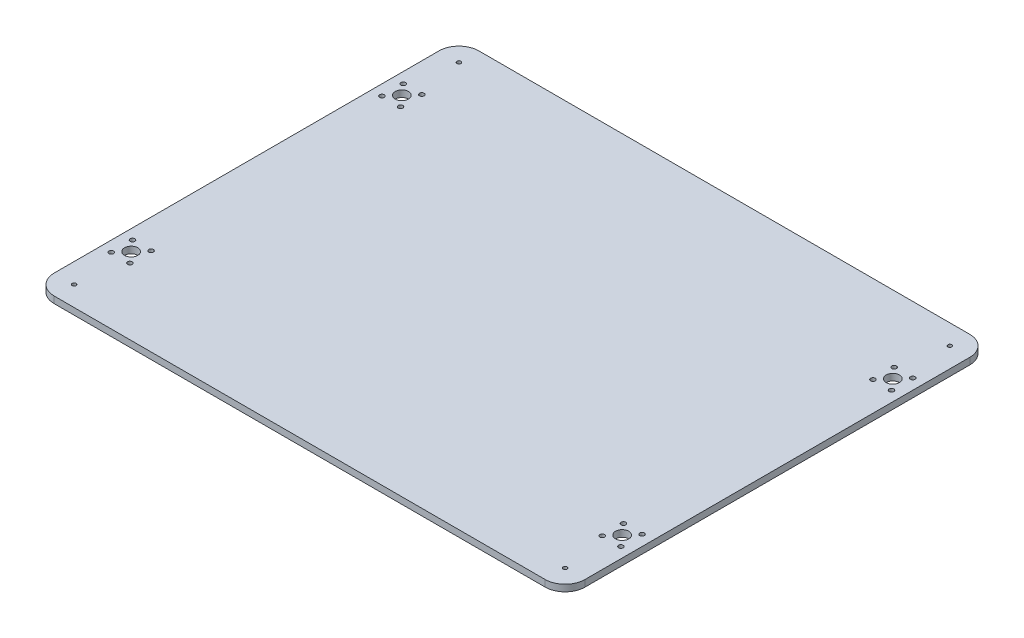
SolidWorks part; units mm, degrees
ref_plane "前视基准面" through (0, 0, 0) normal (0, 0, 1) x (1, 0, 0)
ref_plane "上视基准面" through (0, 0, 0) normal (0, 1, 0) x (1, 0, 0)
ref_plane "右视基准面" through (0, 0, 0) normal (1, 0, 0) x (0, 0, -1)
other "Configuration Table"
sketch "草图1" plane through (0, 0, 0) normal (0, 1, 0) x (1, 0, 0)
  line L0 (0, 160) -> (0, -160) construction
  line L1 (200, 0) -> (200, -160)
  line L2 (-200, 0) -> (-200, 160)
  line L3 (-200, 160) -> (200, 160)
  line L4 (-200, 0) -> (-200, -160)
  line L5 (-200, -160) -> (200, -160)
  line L6 (200, 0) -> (200, 160)
  point P0 (0, 0)
  dimension "D1" = 160
  dimension "D2" = 160
  dimension "D3" = 200
extrude "凸台-拉伸1" add sketch "草图1" along normal blind 5
fillet "圆角1" radius 15 4 edges at (-200, 2.5, -160) (-200, 2.5, 160) (200, 2.5, 160) (200, 2.5, -160)
sketch "草图2" plane through (0, 5, 0) normal (0, 1, 0) x (1, 0, 0)
  line L0 (0, -249.0197) -> (0, 249.0197) construction
  line L1 (-243.4111, 0) -> (243.4111, 0) construction
  line L2 (-203.5, 102) -> (-170, 102) construction
  line L3 (-203.5, 115.1) -> (-203.5, 88.9)
  line L4 (-203.5, 88.9) -> (-170, 88.9)
  line L5 (-170, 88.9) -> (-170, 115.1)
  line L6 (-170, 115.1) -> (-203.5, 115.1)
  line L7 (-185, 100.0219) -> (-185, 103.9781) construction
  line L9 (185, 160) -> (-185, 160) construction
  line L10 (-192, 110) -> (-178, 110) construction
  line L11 (-178, 110) -> (-178, 94) construction
  line L12 (-178, 94) -> (-192, 94) construction
  line L13 (-192, 94) -> (-192, 110) construction
  line L15 (-200, 145) -> (-200, -145) construction
  circle A0 centre (-185, 102) radius 5
  circle A1 centre (-192, 110) radius 1.75
  circle A2 centre (-178, 110) radius 1.75
  circle A3 centre (-178, 94) radius 1.75
  circle A4 centre (-192, 94) radius 1.75
  point P6 (0, 0)
  dimension "D3" = 10
  dimension "D4" = 3.5
  dimension "D5" = 14
  dimension "D6" = 7
  dimension "D7" = 16
  dimension "D8" = 8
  dimension "D9" = 8
  dimension "D10" = 30
  dimension "D11" = 50
  dimension "D1" = 26.2
  dimension "D2" = 33.5
extrude "切除-拉伸2" cut sketch "草图2" against normal through all contours A1 | A2 | A3 | A0 | A4
mirror "镜向1" about plane through (0, 0, 0) normal (1, 0, 0) of "切除-拉伸2" second plane through (0, 0, 0) second plane normal (0, 0, 1)
sketch "草图3" plane through (0, 5, 0) normal (0, 1, 0) x (1, 0, 0)
  line L0 (0, 0) -> (0, -210.3181) construction
  line L1 (0, 0) -> (326.9216, 0) construction
  circle A0 centre (185, -145) radius 1.5
  dimension "D1" = 3
extrude "切除-拉伸3" cut sketch "草图3" against normal through all
mirror "镜向2" about plane through (0, 0, 0) normal (0, 0, 1) of "切除-拉伸3" second plane through (0, 0, 0) second plane normal (1, 0, 0)
